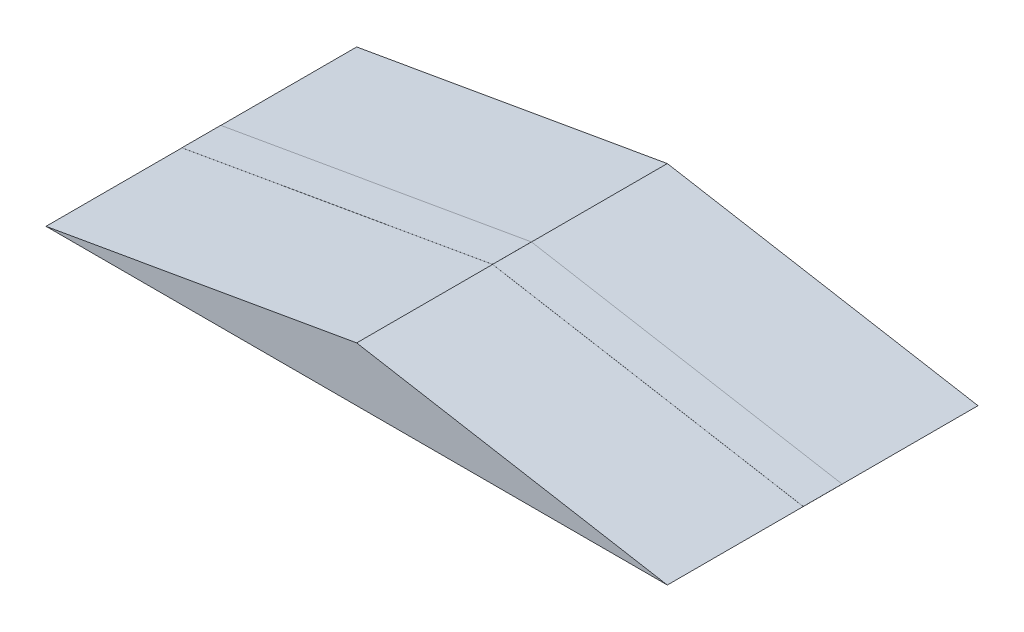
SolidWorks part; units mm, degrees
ref_plane "Спереди" through (0, 0, 0) normal (0, 0, 1) x (1, 0, 0)
ref_plane "Сверху" through (0, 0, 0) normal (0, 1, 0) x (1, 0, 0)
ref_plane "Справа" through (0, 0, 0) normal (1, 0, 0) x (0, 0, -1)
sketch "Эскиз1" plane through (0, 0, 0) normal (0, 0, 1) x (1, 0, 0)
  line L0 (-400, 0) -> (400, 0)
  line L1 (-400, 0) -> (0, 70)
  line L2 (0, 70) -> (0, 0) construction
  line L3 (400, 0) -> (0, 70)
  dimension "D1" = 800
  dimension "D2" = 70
extrude "Бобышка-Вытянуть1" add sketch "Эскиз1" along normal blind 400
sketch "Эскиз2" plane through (11.886, 67.92, 0) normal (0.1724, 0.985, 0) x (0.985, -0.1724, 0)
  line L0 (-12.0666, -400) -> (-12.0666, 0) construction
  line L1 (394.0122, -225) -> (-12.0666, -225)
  line L2 (394.0122, -225) -> (394.0122, -175)
  line L3 (394.0122, -175) -> (-12.0666, -175)
  line L4 (-12.0666, -225) -> (-12.0666, -175)
  line L5 (394.0122, -225) -> (-12.0666, -175) construction
  line L6 (394.0122, -175) -> (-12.0666, -225) construction
  line L7 (394.0122, -400) -> (394.0122, 0) construction
  point P0 (190.9728, -200)
  point P8 (-12.0666, -200)
  dimension "D1" = 50
extrude "Бобышка-Вытянуть2" add sketch "Эскиз2" along normal blind 0.1
mirror "Зеркальное отражение1" about plane through (0, 0, 0) normal (1, 0, 0) of "Бобышка-Вытянуть2"
